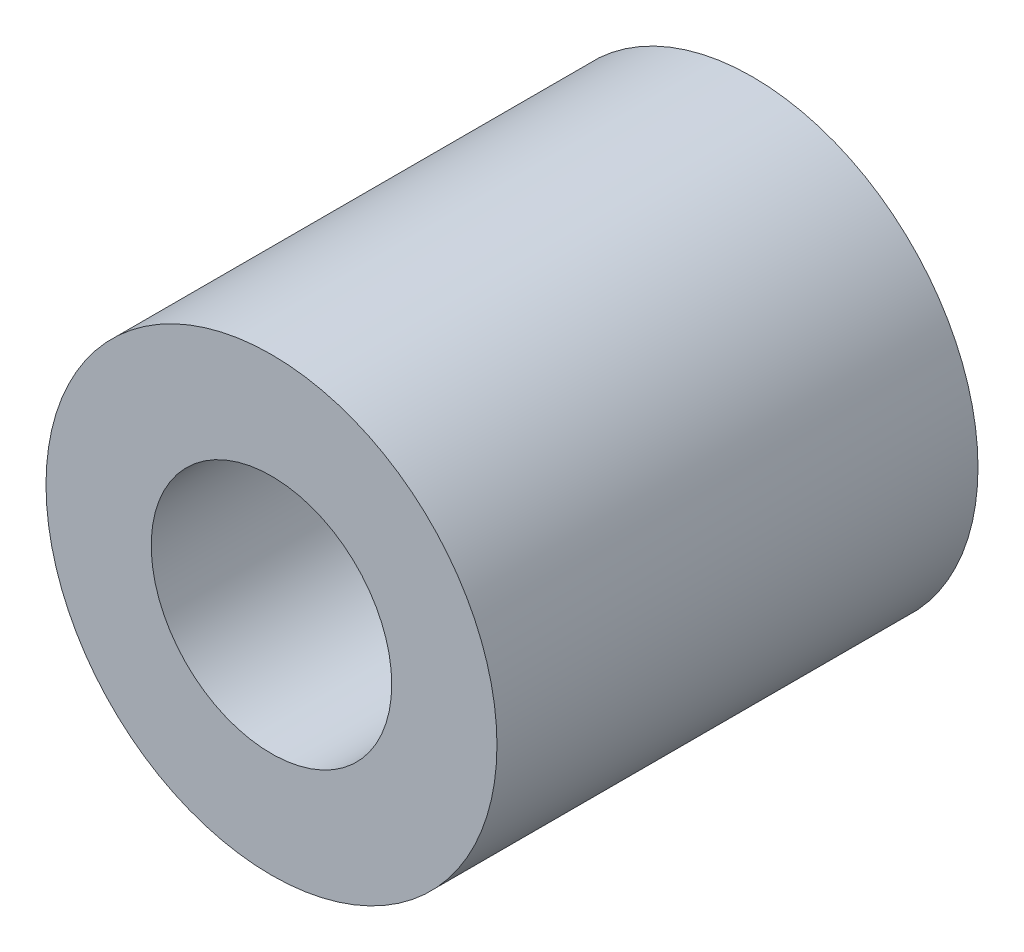
SolidWorks part; units mm, degrees
ref_plane "前视基准面" through (0, 0, 0) normal (0, 0, 1) x (1, 0, 0)
ref_plane "上视基准面" through (0, 0, 0) normal (0, 1, 0) x (1, 0, 0)
ref_plane "右视基准面" through (0, 0, 0) normal (1, 0, 0) x (0, 0, -1)
sketch "草图1" plane through (0, 0, 0) normal (0, 0, 1) x (1, 0, 0)
  circle A0 centre (0, 0) radius 4
  circle A1 centre (0, 0) radius 7.5
extrude "凸台-拉伸1" add sketch "草图1" along normal blind 16
